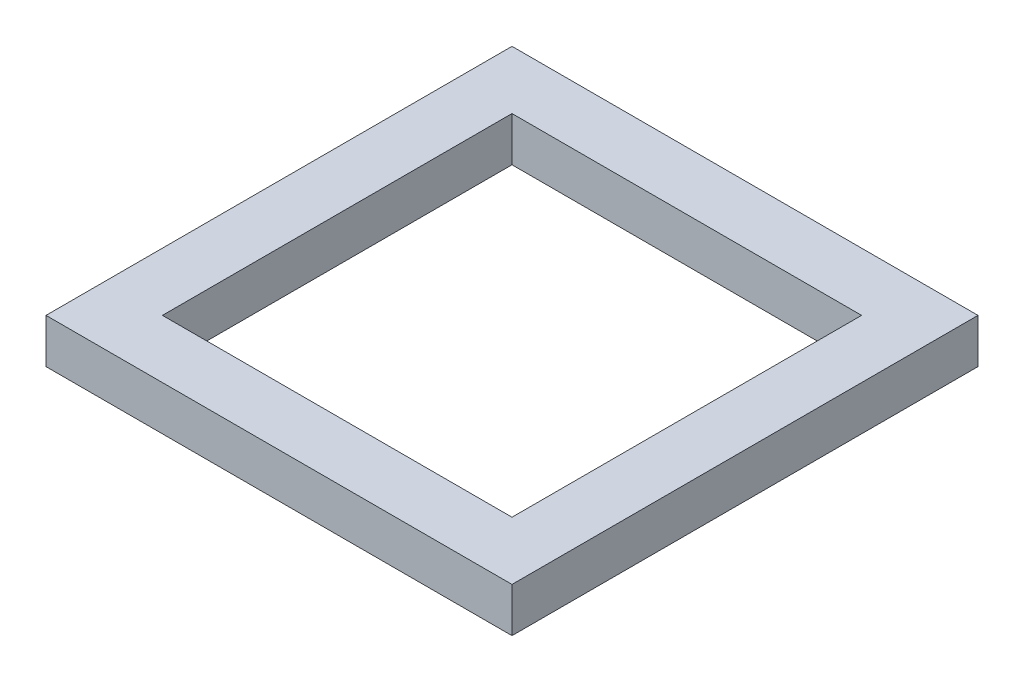
SolidWorks part; units mm, degrees
ref_plane "Front Plane" through (0, 0, 0) normal (0, 0, 1) x (1, 0, 0)
ref_plane "Top Plane" through (0, 0, 0) normal (0, 1, 0) x (1, 0, 0)
ref_plane "Right Plane" through (0, 0, 0) normal (1, 0, 0) x (0, 0, -1)
sketch "Sketch1" plane through (0, 0, 0) normal (0, 1, 0) x (1, 0, 0)
  line L1 (-11.2945, 19.1355) -> (28.7055, 19.1355)
  line L2 (-11.2945, 19.1355) -> (-11.2945, -20.8645)
  line L3 (-11.2945, -20.8645) -> (28.7055, -20.8645)
  line L4 (28.7055, 19.1355) -> (28.7055, -20.8645)
  line L5 (-17.9545, 25.7955) -> (35.3655, 25.7955)
  line L6 (-17.9545, 25.7955) -> (-17.9545, -27.5245)
  line L7 (-17.9545, -27.5245) -> (35.3655, -27.5245)
  line L8 (35.3655, 25.7955) -> (35.3655, -27.5245)
  dimension "D1" = 40
  dimension "D2" = 40
  dimension "D3" = 53.32
  dimension "D4" = 53.32
  dimension "D5" = 6.66
  dimension "D6" = 6.66
extrude "Boss-Extrude1" add sketch "Sketch1" along normal blind 5.08
